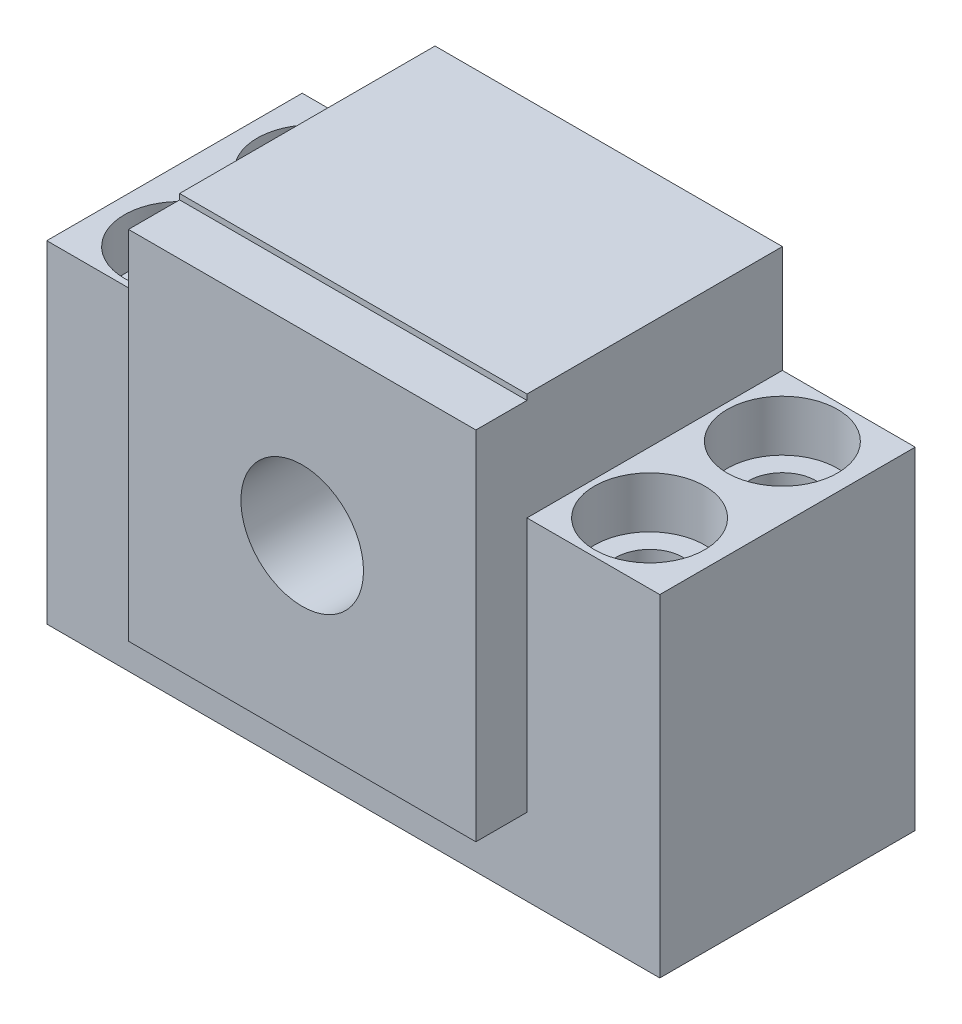
SolidWorks part; units mm, degrees
ref_plane "Plan de face" through (0, 0, 0) normal (0, 0, 1) x (1, 0, 0)
ref_plane "Plan de dessus" through (0, 0, 0) normal (0, 1, 0) x (1, 0, 0)
ref_plane "Plan de droite" through (0, 0, 0) normal (1, 0, 0) x (0, 0, -1)
sketch "Esquisse1" plane through (0, 0, 0) normal (0, 0, 1) x (1, 0, 0)
  line L0 (-27.862, -13.9359) -> (32.138, -13.9359)
  line L1 (32.138, -13.9359) -> (32.138, 18.5641)
  line L2 (32.138, 18.5641) -> (19.138, 18.5641)
  line L3 (19.138, 18.5641) -> (19.138, 29.0641)
  line L4 (19.138, 29.0641) -> (-14.862, 29.0641)
  line L5 (-14.862, 29.0641) -> (-14.862, 18.5641)
  line L6 (-14.862, 18.5641) -> (-27.862, 18.5641)
  line L7 (-27.862, 18.5641) -> (-27.862, -13.9359)
  circle A0 centre (2.138, 11.0641) radius 6
  point P2 (2.138, -13.9359)
  point P9 (2.138, 29.0641)
  dimension "D5" = 12
  dimension "D1" = 60
  dimension "D2" = 34
  dimension "D3" = 32.5
  dimension "D4" = 43
  dimension "D6" = 25
extrude "Boss.-Extru.1" add sketch "Esquisse1" along normal blind 25
sketch "Esquisse2" plane through (0, 18.5641, 0) normal (0, 1, 0) x (1, 0, 0)
  line L1 (32.138, 0) -> (19.138, 0) construction
  line L2 (-20.862, -19) -> (25.138, -19) construction
  line L3 (19.138, -25) -> (-14.862, -25) construction
  circle A0 centre (25.138, -19) radius 3.3
  circle A1 centre (25.138, -6) radius 3.3
  circle A2 centre (-20.862, -19) radius 3.3
  circle A3 centre (-20.862, -6) radius 3.3
  point P8 (2.138, -19)
  point P11 (2.138, -25)
  dimension "D4" = 6.6
  dimension "D1" = 6
  dimension "D2" = 13
  dimension "D3" = 46
extrude "Enlèv. mat.-Extru.1" cut sketch "Esquisse2" against normal up to next
sketch "Esquisse3" plane through (0, 18.5641, 0) normal (0, 1, 0) x (1, 0, 0)
  circle A0 centre (25.138, -19) radius 5.4
  circle A1 centre (25.138, -6) radius 5.4
  circle A2 centre (-20.862, -6) radius 5.4
  circle A3 centre (-20.862, -19) radius 5.4
  dimension "D1" = 10.8
extrude "Enlèv. mat.-Extru.2" cut sketch "Esquisse3" against normal blind 5
sketch "Esquisse4" plane through (0, 0, 25) normal (0, 0, 1) x (1, 0, 0)
  line L0 (-14.862, 28.5194) -> (19.138, -6.3913) construction
  line L1 (-14.862, 28.5194) -> (19.138, 28.5194)
  line L2 (-14.862, 28.5194) -> (-14.862, -6.3913)
  line L3 (-14.862, -6.3913) -> (19.138, -6.3913)
  line L4 (19.138, 28.5194) -> (19.138, -6.3913)
  circle A0 centre (2.138, 11.0641) radius 6 construction
  circle A1 centre (2.138, 11.0641) radius 6
  point P8 (2.138, 11.0641)
  dimension "D1" = 34
extrude "Boss.-Extru.2" add sketch "Esquisse4" along normal blind 5
